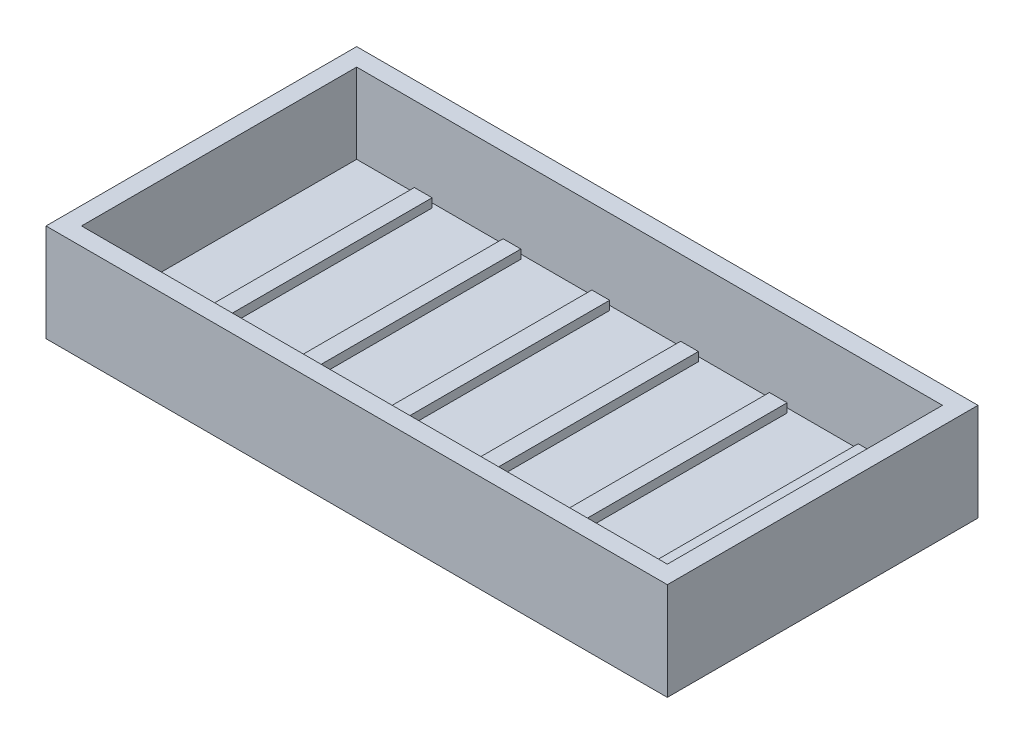
SolidWorks part; units mm, degrees
ref_plane "Front Plane" through (0, 0, 0) normal (0, 0, 1) x (1, 0, 0)
ref_plane "Top Plane" through (0, 0, 0) normal (0, 1, 0) x (1, 0, 0)
ref_plane "Right Plane" through (0, 0, 0) normal (1, 0, 0) x (0, 0, -1)
other "Configuration Table"
sketch "Sketch1" plane through (0, 0, 0) normal (0, 1, 0) x (1, 0, 0)
  line L0 (-70, -70) -> (70, -70)
  line L1 (70, -70) -> (70, 0)
  line L2 (70, 0) -> (-70, 0)
  line L3 (-70, 0) -> (-70, -70)
extrude "Tray" add sketch "Sketch1" along normal blind 22
sketch "Sketch2" plane through (0, 0, 0) normal (0, 1, 0) x (1, 0, 0)
  line L0 (-66, -66) -> (66, -66)
  line L1 (66, -66) -> (66, -4)
  line L2 (66, -4) -> (-66, -4)
  line L3 (-66, -4) -> (-66, -66)
extrude "Basin" cut sketch "Sketch2" against normal blind 18 from offset 22
sketch "Sketch3" plane through (0, 0, 0) normal (0, 1, 0) x (1, 0, 0)
  line L0 (-52, -65) -> (-48, -65)
  line L1 (-48, -65) -> (-48, -5)
  line L2 (-48, -5) -> (-52, -5)
  line L3 (-52, -5) -> (-52, -65)
  line L4 (-32, -65) -> (-28, -65)
  line L5 (-28, -65) -> (-28, -5)
  line L6 (-28, -5) -> (-32, -5)
  line L7 (-32, -5) -> (-32, -65)
  line L8 (-12, -65) -> (-8, -65)
  line L9 (-8, -65) -> (-8, -5)
  line L10 (-8, -5) -> (-12, -5)
  line L11 (-12, -5) -> (-12, -65)
  line L12 (8, -65) -> (12, -65)
  line L13 (12, -65) -> (12, -5)
  line L14 (12, -5) -> (8, -5)
  line L15 (8, -5) -> (8, -65)
  line L16 (28, -65) -> (32, -65)
  line L17 (32, -65) -> (32, -5)
  line L18 (32, -5) -> (28, -5)
  line L19 (28, -5) -> (28, -65)
  line L20 (48, -65) -> (52, -65)
  line L21 (52, -65) -> (52, -5)
  line L22 (52, -5) -> (48, -5)
  line L23 (48, -5) -> (48, -65)
extrude "Grille_Ribs" add sketch "Sketch3" along normal blind 2 from offset 4
equation "\"Jar_OD\"= 90  'ASSUMED - Part G fallback - jar outer diameter"
equation "\"Jar_H\"= 120  'ASSUMED - Part G fallback - jar height"
equation "\"Pump_L\"= 45  'ASSUMED - Part G fallback"
equation "\"Pump_W\"= 24  'ASSUMED - Part G fallback"
equation "\"Pump_H\"= 33  'ASSUMED - Part G fallback"
equation "\"Pump_Outlet_OD\"= 7.5  'ASSUMED - Part G fallback"
equation "\"Tube_OD\"= 8  'ASSUMED - Part G fallback"
equation "\"Tube_ID\"= 6  'ASSUMED - Part G fallback"
equation "\"TDS_Body_Dia\"= 12  'ASSUMED - Part G fallback"
equation "\"TDS_Wet_Len\"= 45  'ASSUMED - Part G fallback - length in water"
equation "\"DS_Tube_Dia\"= 6  'ASSUMED - Part G fallback"
equation "\"DS_Tube_Len\"= 50  'ASSUMED - Part G fallback"
equation "\"ORP_Body_Dia\"= 12  'ASSUMED - Part G fallback"
equation "\"ORP_Body_Len\"= 150  'ASSUMED - Part G fallback"
equation "\"ORP_Cap_Dia\"= 16  'ASSUMED - Part G fallback"
equation "\"Turb_W\"= 33  'ASSUMED - Part G fallback - head width"
equation "\"Turb_D\"= 28  'ASSUMED - Part G fallback - head depth"
equation "\"Turb_H\"= 30  'ASSUMED - Part G fallback - head height"
equation "\"Turb_Slot_W\"= 10  'ASSUMED - Part G fallback - slot width"
equation "\"Flow_L\"= 62  'ASSUMED - Part G fallback YF-S201"
equation "\"Flow_W\"= 36  'ASSUMED - Part G fallback"
equation "\"Flow_H\"= 35  'ASSUMED - Part G fallback"
equation "\"Thread_G12_OD\"= 20.955  'ASSUMED - Part G fallback thread G1/2 (major diameter)"
equation "\"Valve_L\"= 75  'ASSUMED - Part G fallback"
equation "\"Valve_W\"= 45  'ASSUMED - Part G fallback"
equation "\"Valve_H\"= 60  'ASSUMED - Part G fallback"
equation "\"Tee_L\"= 40  'ASSUMED - Part G fallback - overall length"
equation "\"Tee_Branch_L\"= 25  'ASSUMED - Part G fallback"
equation "\"Tee_OD\"= 12  'ASSUMED - Part G fallback"
equation "\"LED_Board_L\"= 20  'ASSUMED - Part G fallback"
equation "\"LED_Board_W\"= 20  'ASSUMED - Part G fallback - LED at centre"
equation "\"GUVA_L\"= 20  'ASSUMED - Part G fallback"
equation "\"GUVA_W\"= 12  'ASSUMED - Part G fallback - sensor at centre"
equation "\"Reed_L\"= 27  'ASSUMED - Part G fallback MC-38 half"
equation "\"Reed_W\"= 14  'ASSUMED - Part G fallback"
equation "\"Reed_H\"= 8  'ASSUMED - Part G fallback"
equation "\"ESP_L\"= 51  'ASSUMED - Part G fallback"
equation "\"ESP_W\"= 28  'ASSUMED - Part G fallback"
equation "\"TFT_L\"= 58  'ASSUMED - Part G fallback - board"
equation "\"TFT_W\"= 35  'ASSUMED - Part G fallback - board"
equation "\"TFT_Win_L\"= 35  'ASSUMED - Part G fallback - visible window"
equation "\"TFT_Win_W\"= 28  'ASSUMED - Part G fallback - visible window"
equation "\"Relay_L\"= 50  'ASSUMED - Part G fallback"
equation "\"Relay_W\"= 26  'ASSUMED - Part G fallback"
equation "\"Relay_H\"= 19  'ASSUMED - Part G fallback"
equation "\"Mosfet_L\"= 34  'ASSUMED - Part G fallback"
equation "\"Mosfet_W\"= 17  'ASSUMED - Part G fallback"
equation "\"Mosfet_H\"= 12  'ASSUMED - Part G fallback"
equation "\"TDS_Board_L\"= 42  'ASSUMED - Part G fallback"
equation "\"TDS_Board_W\"= 32  'ASSUMED - Part G fallback"
equation "\"Turb_Board_L\"= 38  'ASSUMED - Part G fallback"
equation "\"Turb_Board_W\"= 28  'ASSUMED - Part G fallback"
equation "\"BNC_Thread_Dia\"= 9.5  'ASSUMED - Part G fallback"
equation "\"Plate_L\"= 420  'ASSUMED - Part G fallback"
equation "\"Plate_W\"= 297  'ASSUMED - Part G fallback"
equation "\"Plate_T\"= 6  'ASSUMED - Part G fallback"
equation "\"Booster_L\"= 150  'ASSUMED - Part G fallback - booster pump"
equation "\"Booster_W\"= 95  'ASSUMED - Part G fallback"
equation "\"Booster_H\"= 100  'ASSUMED - Part G fallback"
equation "\"PTube_OD\"= 6.35  'ASSUMED - Part G fallback - product tube 1/4 inch"
equation "\"Qz_Out\"= 12  'ASSUMED - Part G fallback - quartz channel outside square"
equation "\"Qz_Path\"= 10  'ASSUMED - Part G fallback - quartz channel inside light path"
equation "\"Qz_L\"= 40  'ASSUMED - Part G fallback - quartz channel length"
equation "\"LED860_Dia\"= 5  'ASSUMED - Part G fallback - 860 nm LED"
equation "\"BPW_L\"= 5.4  'ASSUMED - Part G fallback - BPW34"
equation "\"BPW_W\"= 4.3  'ASSUMED - Part G fallback - BPW34"
equation "\"Cart_Dia\"= 50  'ASSUMED - Part G fallback - sediment and pre-carbon cartridges"
equation "\"Cart_L\"= 255  'ASSUMED - Part G fallback"
equation "\"UF_Dia\"= 50  'ASSUMED - Part G fallback - UF cartridge"
equation "\"UF_L\"= 260  'ASSUMED - Part G fallback"
equation "\"RO_Dia\"= 62  'ASSUMED - Part G fallback - RO membrane housing"
equation "\"RO_L\"= 300  'ASSUMED - Part G fallback"
equation "\"UVC_Dia\"= 40  'ASSUMED - Part G fallback - UV-C chamber"
equation "\"UVC_L\"= 300  'ASSUMED - Part G fallback"
equation "\"Tank_W\"= 260  'ASSUMED - Part G fallback - storage tank"
equation "\"Tank_D\"= 160  'ASSUMED - Part G fallback"
equation "\"Tank_H\"= 300  'ASSUMED - Part G fallback"
equation "\"Cab_W\"= 400  'ASSUMED - Part G fallback - purifier cabinet"
equation "\"Cab_D\"= 270  'ASSUMED - Part G fallback"
equation "\"Cab_H\"= 560  'ASSUMED - Part G fallback"
equation "\"ORP_Board_L\"= 40  'ASSUMED - Part G fallback - ORP buffer board"
equation "\"ORP_Board_W\"= 30  'ASSUMED - Part G fallback"
equation "\"Opt_Board_L\"= 50  'ASSUMED - Part G fallback - optical front-end board"
equation "\"Opt_Board_W\"= 40  'ASSUMED - Part G fallback"
equation "\"Buck_L\"= 43  'ASSUMED - Part G fallback - 12 V to 5 V buck module"
equation "\"Buck_W\"= 21  'ASSUMED - Part G fallback"
equation "\"Buck_H\"= 14  'ASSUMED - Part G fallback"
equation "\"BB_L\"= 165  'ASSUMED - Part G fallback - breadboard (As_Built_R3 only)"
equation "\"BB_W\"= 55  'ASSUMED - Part G fallback"
equation "\"BB_H\"= 10  'ASSUMED - Part G fallback"
equation "\"Cuv_W\"= 12.5  'ASSUMED - old R3 cuvette (station suppressed in SS4)"
equation "\"Cuv_D\"= 12.5  'ASSUMED - old R3 cuvette (station suppressed in SS4)"
equation "\"Cuv_H\"= 45  'ASSUMED - old R3 cuvette (station suppressed in SS4)"
equation "\"Probe_Clr\"= 0.3  'DESIGN VALUE - Part C rule 3 - printed probe hole = diameter + 0.3"
equation "\"Label_H\"= 0.6  'DESIGN VALUE - Part D - raised label height"
